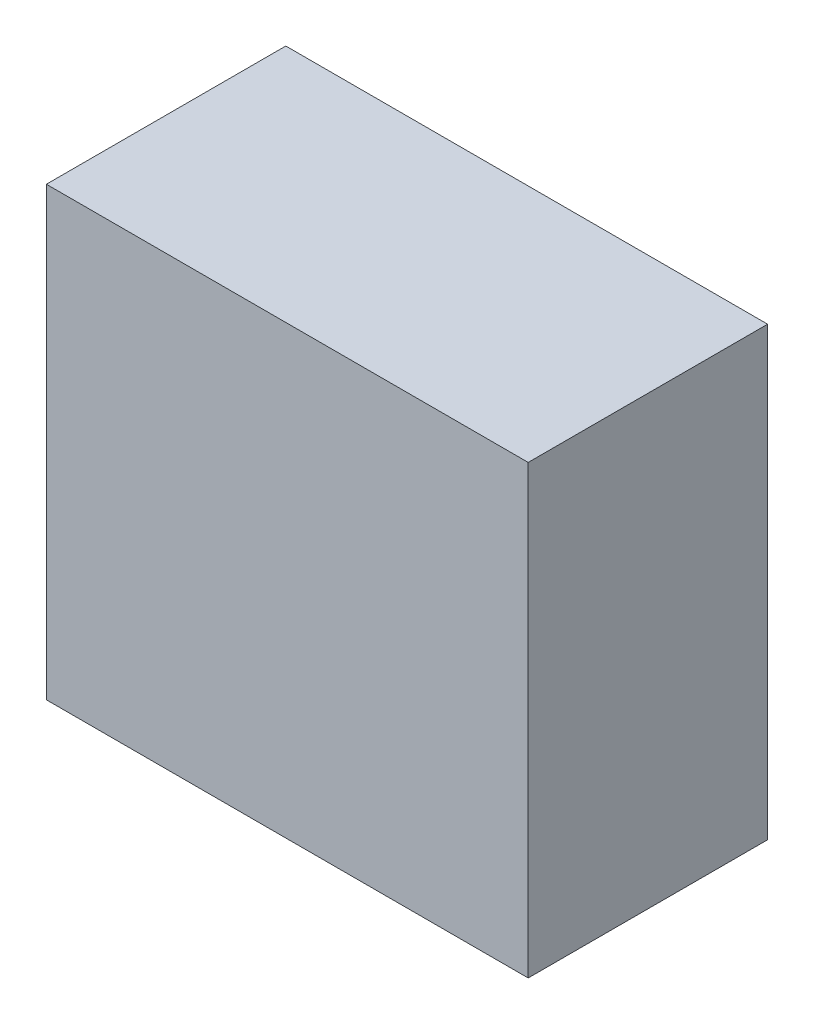
SolidWorks part; units mm, degrees
ref_plane "Front Plane" through (0, 0, 0) normal (0, 0, 1) x (1, 0, 0)
ref_plane "Top Plane" through (0, 0, 0) normal (0, 1, 0) x (1, 0, 0)
ref_plane "Right Plane" through (0, 0, 0) normal (1, 0, 0) x (0, 0, -1)
ref_plane "Plane1" through (0, 0, 10) normal (0, 0, 1) x (1, 0, 0)
sketch "Sketch1" plane through (0, 0, 10) normal (0, 0, 1) x (1, 0, 0)
  line L0 (-20.125, 37.3) -> (-20.125, 0)
  line L1 (-20.125, 0) -> (20.125, 0)
  line L2 (20.125, 0) -> (20.125, 37.3)
  line L3 (20.125, 37.3) -> (-20.125, 37.3)
extrude "Boss-Extrude1" add sketch "Sketch1" against normal blind 20
